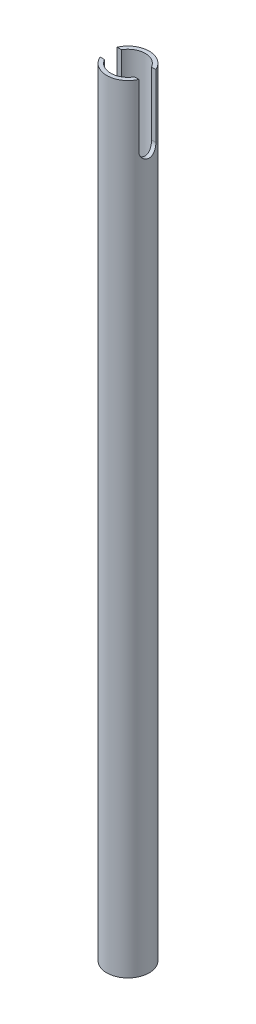
SolidWorks part; units mm, degrees
material "AISI 4130 Steel, annealed at 865C"
ref_plane "X-Y Datum" through (0, 0, 0) normal (0, 0, 1) x (1, 0, 0)
ref_plane "X-Z Datum" through (0, 0, 0) normal (0, 1, 0) x (1, 0, 0)
ref_plane "Y-Z Datum" through (0, 0, 0) normal (1, 0, 0) x (0, 0, -1)
sketch "Sketch1" plane through (0, 0, 0) normal (0, 1, 0) x (1, 0, 0)
  circle A0 centre (0, 0) radius 7.9375
  circle A1 centre (0, 0) radius 6.4643
  dimension "D1" = 15.875
  dimension "D2" = 1.4732
extrude "Boss-Extrude1" add sketch "Sketch1" along normal offset from surface (291.329 mm away) 25.4
sketch "Sketch4" plane through (0, 0, 0) normal (1, 0, 0) x (0, 0, -1)
  line L5 (0, 318.492) -> (0, 267.692) construction
  line L7 (3.175, 318.492) -> (3.175, 267.692)
  line L8 (-3.175, 318.492) -> (-3.175, 267.692)
  arc A0 (3.175, 318.492) -> (-3.175, 318.492) centre (0, 318.492) ccw
  arc A1 (-3.175, 267.692) -> (3.175, 267.692) centre (0, 267.692) ccw
  point P4 (0, 293.092)
  dimension "D1" = 6.35
  dimension "D2" = 25.4
extrude "Cut-Extrude1" cut sketch "Sketch4" against normal through all both and the other way through all
